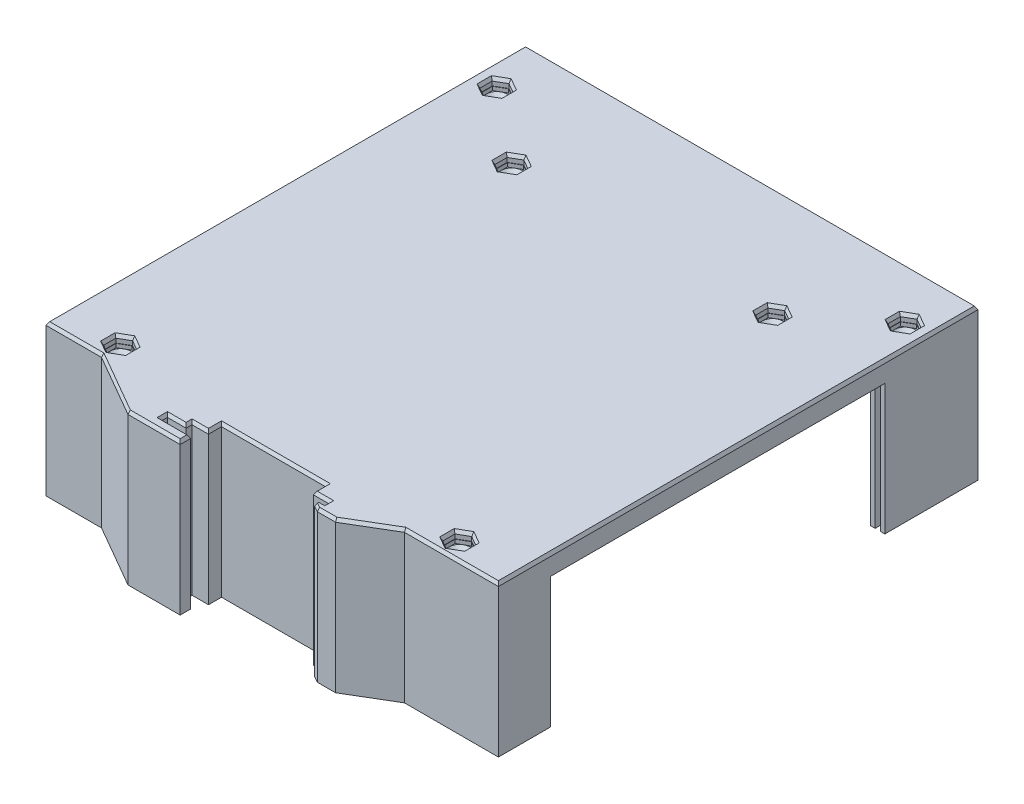
SolidWorks part; units mm, degrees
ref_plane "Спереди" through (0, 0, 0) normal (0, 0, 1) x (1, 0, 0)
ref_plane "Сверху" through (0, 0, 0) normal (0, 1, 0) x (1, 0, 0)
ref_plane "Справа" through (0, 0, 0) normal (1, 0, 0) x (0, 0, -1)
sketch "Эскиз1" plane through (0, 0, 0) normal (0, 1, 0) x (1, 0, 0)
  line L0 (0, 0) -> (0, 128.7)
  line L1 (0, 128.7) -> (121.4, 128.7)
  line L2 (121.4, 128.7) -> (121.4, 0)
  line L3 (121.4, 0) -> (0, 0)
  dimension "D1" = 128.7
  dimension "D2" = 121.4
extrude "Бобышка-Вытянуть1" add sketch "Эскиз1" along normal blind 1.5
sketch "Эскиз2" plane through (0, 0, 0) normal (0, -1, 0) x (1, 0, 0)
  line L0 (121.4, 0) -> (121.4, -128.7)
  line L1 (121.4, -128.7) -> (0, -128.7)
  line L2 (0, -128.7) -> (0, 0)
  line L3 (0, 0) -> (121.4, 0)
  line L4 (117.6, -124.9) -> (117.6, -8)
  line L5 (117.6, -8) -> (3.8, -8)
  line L6 (3.8, -8) -> (3.8, -124.9)
  line L7 (3.8, -124.9) -> (117.6, -124.9)
  line L8 (119.7, -6.3) -> (119.7, -1.7)
  line L9 (119.7, -1.7) -> (83.7, -1.7)
  line L10 (1.7, -1.7) -> (1.7, -6.3)
  line L11 (1.7, -6.3) -> (37.7, -6.3)
  line L12 (61.7, -6.3) -> (61.7, -1.7)
  line L13 (59.7, -6.3) -> (59.7, -1.7)
  line L14 (61.7, -6.3) -> (81.7, -6.3)
  line L15 (59.7, -1.7) -> (39.7, -1.7)
  line L16 (81.7, -6.3) -> (81.7, -1.7)
  line L17 (83.7, -6.3) -> (83.7, -1.7)
  line L18 (39.7, -6.3) -> (39.7, -1.7)
  line L19 (37.7, -1.7) -> (37.7, -6.3)
  line L20 (81.7, -1.7) -> (61.7, -1.7)
  line L21 (83.7, -6.3) -> (119.7, -6.3)
  line L22 (37.7, -1.7) -> (1.7, -1.7)
  line L23 (39.7, -6.3) -> (59.7, -6.3)
  line L24 (61.7, -1.7) -> (59.7, -1.7) construction
  line L25 (60.7, -1.7) -> (60.7, 0) construction
  point P28 (83.7, -4)
  dimension "D1" = 8
  dimension "D2" = 3.8
  dimension "D3" = 3.8
  dimension "D4" = 3.8
  dimension "D5" = 1.7
  dimension "D6" = 1.7
  dimension "D7" = 1.7
  dimension "D8" = 1.7
  dimension "D10" = 2
  dimension "D11" = 2
  dimension "D12" = 2
  dimension "D13" = 20
  dimension "D14" = 20
extrude "Бобышка-Вытянуть2" add sketch "Эскиз2" along normal blind 2
sketch "Эскиз3" plane through (0, -2, 0) normal (0, -1, 0) x (1, 0, 0)
  line L0 (117.6, -8) -> (121.4, -8)
  line L1 (121.4, -128.7) -> (121.4, 0) construction
  line L2 (121.4, -8) -> (121.4, -128.7)
  line L3 (121.4, -128.7) -> (0, -128.7)
  line L4 (0, -128.7) -> (0, -8)
  line L5 (0, 0) -> (0, -128.7) construction
  line L6 (0, -8) -> (3.8, -8)
  line L7 (3.8, -8) -> (3.8, -124.9)
  line L8 (3.8, -124.9) -> (117.6, -124.9)
  line L9 (117.6, -124.9) -> (117.6, -8)
  line L10 (120.3, -10.6) -> (118.8, -10.6)
  line L11 (118.8, -10.6) -> (118.8, -107.4)
  line L12 (118.8, -107.4) -> (120.3, -107.4)
  line L13 (120.3, -107.4) -> (120.3, -10.6)
  line L14 (117.6, -8) -> (3.8, -8) construction
  line L16 (117.6, -127.6) -> (3.8, -127.6)
  line L17 (117.6, -127.6) -> (117.6, -126.1)
  line L18 (117.6, -126.1) -> (3.8, -126.1)
  line L19 (3.8, -127.6) -> (3.8, -126.1)
  line L20 (2.6, -107.4) -> (1.1, -107.4)
  line L21 (2.6, -107.4) -> (2.6, -10.6)
  line L22 (2.6, -10.6) -> (1.1, -10.6)
  line L23 (1.1, -107.4) -> (1.1, -10.6)
  dimension "D1" = 2.6
  dimension "D2" = 1.5
  dimension "D3" = 1.1
  dimension "D4" = 21.3
  dimension "D5" = 3.8
  dimension "D6" = 1.1
  dimension "D7" = 1.5
  dimension "D8" = 3.8
  dimension "D9" = 21.3
  dimension "D10" = 2.6
  dimension "D11" = 1.1
  dimension "D12" = 1.5
extrude "Бобышка-Вытянуть3" add sketch "Эскиз3" along normal blind 2
sketch "Эскиз4" plane through (0, -4, 0) normal (0, -1, 0) x (1, 0, 0)
  line L0 (121.4, -8) -> (121.4, -14)
  line L1 (121.4, -128.7) -> (121.4, -8) construction
  line L2 (121.4, -14) -> (120.3, -14)
  line L3 (117.6, -124.9) -> (117.6, -8) construction
  line L4 (117.6, -14) -> (117.6, -8)
  line L5 (117.6, -8) -> (121.4, -8)
  line L6 (120.3, -14) -> (120.3, -10.6)
  line L7 (120.3, -107.4) -> (120.3, -10.6) construction
  line L8 (120.3, -10.6) -> (118.8, -10.6)
  line L9 (118.8, -10.6) -> (118.8, -14)
  line L10 (118.8, -10.6) -> (118.8, -107.4) construction
  line L11 (118.8, -14) -> (117.6, -14)
  line L12 (3.8, -8) -> (0, -8)
  line L13 (0, -8) -> (0, -14)
  line L14 (0, -8) -> (0, -128.7) construction
  line L15 (0, -14) -> (1.1, -14)
  line L16 (3.8, -8) -> (3.8, -124.9) construction
  line L17 (3.8, -14) -> (3.8, -8)
  line L18 (2.6, -14) -> (2.6, -10.6)
  line L19 (2.6, -107.4) -> (2.6, -10.6) construction
  line L20 (2.6, -10.6) -> (1.1, -10.6)
  line L21 (1.1, -10.6) -> (1.1, -14)
  line L22 (1.1, -10.6) -> (1.1, -107.4) construction
  line L23 (2.6, -14) -> (3.8, -14)
  line L24 (121.4, -128.7) -> (121.4, -103.7)
  line L25 (121.4, -103.7) -> (120.3, -103.7)
  line L26 (117.6, -8) -> (117.6, -124.9) construction
  line L27 (117.6, -103.7) -> (117.6, -124.9)
  line L28 (117.6, -124.9) -> (113.4, -124.9)
  line L29 (3.8, -124.9) -> (117.6, -124.9) construction
  line L30 (113.4, -124.9) -> (113.4, -126.1)
  line L31 (0, -128.7) -> (121.4, -128.7) construction
  line L32 (113.4, -128.7) -> (121.4, -128.7)
  line L33 (120.3, -103.7) -> (120.3, -107.4)
  line L34 (120.3, -107.4) -> (120.3, -10.6) construction
  line L35 (120.3, -107.4) -> (118.8, -107.4)
  line L36 (118.8, -107.4) -> (118.8, -103.7)
  line L37 (118.8, -10.6) -> (118.8, -107.4) construction
  line L38 (113.4, -127.6) -> (117.6, -127.6)
  line L39 (3.8, -127.6) -> (117.6, -127.6) construction
  line L40 (117.6, -127.6) -> (117.6, -126.1)
  line L41 (117.6, -126.1) -> (113.4, -126.1)
  line L42 (117.6, -126.1) -> (3.8, -126.1) construction
  line L43 (113.4, -127.6) -> (113.4, -128.7)
  line L44 (118.8, -103.7) -> (117.6, -103.7)
  line L45 (8, -124.9) -> (3.8, -124.9)
  line L46 (3.8, -124.9) -> (3.8, -103.7)
  line L47 (3.8, -103.7) -> (2.6, -103.7)
  line L48 (0, -103.7) -> (0, -128.7)
  line L49 (0, -128.7) -> (8, -128.7)
  line L50 (8, -128.7) -> (8, -127.6)
  line L51 (8, -127.6) -> (3.8, -127.6)
  line L52 (3.8, -127.6) -> (117.6, -127.6) construction
  line L53 (3.8, -127.6) -> (3.8, -126.1)
  line L54 (3.8, -126.1) -> (8, -126.1)
  line L55 (117.6, -126.1) -> (3.8, -126.1) construction
  line L56 (2.6, -103.7) -> (2.6, -107.4)
  line L57 (2.6, -107.4) -> (1.1, -107.4)
  line L58 (1.1, -107.4) -> (1.1, -103.7)
  line L59 (1.1, -10.6) -> (1.1, -107.4) construction
  line L60 (1.1, -103.7) -> (0, -103.7)
  line L61 (8, -126.1) -> (8, -124.9)
  dimension "D1" = 6
  dimension "D2" = 6
  dimension "D3" = 25
  dimension "D4" = 8
  dimension "D5" = 8
  dimension "D6" = 25
extrude "Бобышка-Вытянуть4" add sketch "Эскиз4" along normal blind 35
sketch "Эскиз5" plane through (0, 0, 0) normal (0, -1, 0) x (1, 0, 0)
  line L0 (121.4, -8) -> (121.4, 0) construction
  line L1 (0, 0) -> (0, -8) construction
  line L2 (121.4, 0) -> (0, 0) construction
  line L3 (121.4, -128.7) -> (121.4, -103.7) construction
  line L4 (0, -103.7) -> (0, -128.7) construction
  line L5 (0, -128.7) -> (8, -128.7) construction
  circle A0 centre (106.2, -4.75) radius 3.15
  circle A1 centre (15.2, -4.75) radius 3.15
  circle A2 centre (115.45, -115) radius 3.15
  circle A3 centre (5.95, -115) radius 3.15
  dimension "D1" = 6.3
  dimension "D2" = 15.2
  dimension "D3" = 15.2
  dimension "D4" = 4.75
  dimension "D5" = 5.95
  dimension "D6" = 5.95
  dimension "D7" = 13.7
extrude "Бобышка-Вытянуть5" add sketch "Эскиз5" along normal up to surface (39 mm away) up to face at (117.5, -39, -117.4429)
sketch "Эскиз6" plane through (0, 0, 0) normal (0, -1, 0) x (1, 0, 0)
  circle A0 centre (115.45, -115) radius 4.75
  circle A2 centre (106.2, -4.75) radius 4.75
  circle A3 centre (15.2, -4.75) radius 4.75
  circle A4 centre (5.95, -115) radius 4.75
  dimension "D1" = 9.5
extrude "Бобышка-Вытянуть6" add sketch "Эскиз6" along normal up to surface (4 mm away) up to face at (118.2, -4, -58.85)
sketch "Эскиз7" plane through (0, -2, 0) normal (0, -1, 0) x (1, 0, 0)
  line L0 (121.4, -8) -> (121.4, 0)
  line L1 (121.4, 0) -> (0, 0)
  line L2 (0, 0) -> (0, -8)
  line L3 (0, -8) -> (121.4, -8)
  line L4 (119.7, -6.3) -> (119.7, -1.7)
  line L5 (119.7, -1.7) -> (83.7, -1.7)
  line L6 (83.7, -1.7) -> (83.7, -6.3)
  line L7 (83.7, -6.3) -> (119.7, -6.3)
  line L8 (81.7, -6.3) -> (81.7, -1.7)
  line L9 (81.7, -1.7) -> (61.7, -1.7)
  line L10 (61.7, -1.7) -> (61.7, -6.3)
  line L11 (61.7, -6.3) -> (81.7, -6.3) construction
  line L12 (61.7, -1.7) -> (61.7, -6.3) construction
  line L13 (61.7, -6.3) -> (81.7, -6.3)
  line L14 (59.7, -6.3) -> (59.7, -1.7)
  line L15 (59.7, -1.7) -> (39.7, -1.7)
  line L16 (39.7, -1.7) -> (39.7, -6.3)
  line L17 (39.7, -6.3) -> (59.7, -6.3)
  line L18 (37.7, -6.3) -> (37.7, -1.7)
  line L19 (37.7, -1.7) -> (1.7, -1.7)
  line L20 (1.7, -1.7) -> (1.7, -6.3)
  line L21 (1.7, -6.3) -> (37.7, -6.3)
extrude "Бобышка-Вытянуть7" add sketch "Эскиз7" along normal up to surface (37 mm away) up to face at (119.525, -39, -11.65)
sketch "Эскиз8" plane through (0, -39, 0) normal (0, -1, 0) x (1, 0, 0)
  line L0 (83.7, -8) -> (83.7, -1.7)
  line L1 (83.7, -1.7) -> (81.7, -1.7)
  line L2 (81.7, -1.7) -> (81.7, -6.3)
  line L4 (39.7, -6.3) -> (39.7, -1.7)
  line L5 (39.7, -1.7) -> (37.7, -1.7)
  line L6 (37.7, -1.7) -> (37.7, -8)
  line L8 (81.7, -6.3) -> (39.7, -6.3)
  line L9 (37.7, -8) -> (83.7, -8)
  line L11 (117.6, -8) -> (3.8, -8) construction
extrude "Бобышка-Вытянуть15" add sketch "Эскиз8" along normal blind 3.8
sketch "Эскиз9" plane through (0, 0, 0) normal (0, -1, 0) x (1, 0, 0)
  line L0 (3.8, -124.9) -> (117.6, -124.9) construction
  line L1 (61.8, -124.9) -> (59.6, -124.9)
  line L2 (61.8, -124.9) -> (61.8, -122.7)
  line L3 (61.8, -122.7) -> (59.6, -122.7)
  line L4 (59.6, -124.9) -> (59.6, -122.7)
  line L5 (117.6, -110.7644) -> (117.6, -8) construction
  line L6 (104, -124.9) -> (101.8, -124.9)
  line L7 (104, -124.9) -> (104, -122.7)
  line L8 (104, -122.7) -> (101.8, -122.7)
  line L9 (101.8, -124.9) -> (101.8, -122.7)
  line L10 (19.6, -124.9) -> (17.4, -124.9)
  line L11 (19.6, -124.9) -> (19.6, -122.7)
  line L12 (19.6, -122.7) -> (17.4, -122.7)
  line L13 (17.4, -124.9) -> (17.4, -122.7)
  line L14 (117.6, -100.4) -> (115.4, -100.4)
  line L15 (117.6, -100.4) -> (117.6, -98.2)
  line L16 (117.6, -98.2) -> (115.4, -98.2)
  line L17 (115.4, -100.4) -> (115.4, -98.2)
  line L18 (117.6, -8) -> (83.7, -8) construction
  line L19 (117.6, -16) -> (115.4, -16)
  line L20 (117.6, -16) -> (117.6, -18.2)
  line L21 (117.6, -18.2) -> (115.4, -18.2)
  line L22 (115.4, -16) -> (115.4, -18.2)
  line L23 (61.8, -8) -> (59.6, -8)
  line L24 (61.8, -8) -> (61.8, -10.2)
  line L25 (61.8, -10.2) -> (59.6, -10.2)
  line L26 (59.6, -8) -> (59.6, -10.2)
  line L27 (3.8, -8) -> (3.8, -110.7644) construction
  line L28 (3.8, -16) -> (6, -16)
  line L29 (3.8, -16) -> (3.8, -18.2)
  line L30 (3.8, -18.2) -> (6, -18.2)
  line L31 (6, -16) -> (6, -18.2)
  line L32 (95.7, -99.24) -> (25.7, -99.24) construction
  line L33 (3.8, -100.4) -> (6, -100.4)
  line L34 (3.8, -100.4) -> (3.8, -98.2)
  line L35 (3.8, -98.2) -> (6, -98.2)
  line L36 (6, -100.4) -> (6, -98.2)
  line L37 (60.7, -8) -> (60.7, 0) construction
  line L38 (0, 0) -> (121.4, 0) construction
  line L39 (117.6, -8) -> (109.6641, -8) construction
  line L42 (8, -128.7) -> (113.4, -128.7) construction
  line L43 (60.7, -128.7) -> (60.7, -99.24) construction
  circle A0 centre (95.7, -99.24) radius 4.75
  circle A1 centre (25.7, -99.24) radius 4.75
  point P40 (116.5, -98.2)
  point P41 (116.5, -18.2)
  point P46 (6, -17.1)
  point P49 (116.5, -16)
  dimension "D15" = 9.5
  dimension "D1" = 2.2
  dimension "D2" = 2.2
  dimension "D3" = 2.2
  dimension "D4" = 2.2
  dimension "D5" = 2.2
  dimension "D6" = 2.2
  dimension "D7" = 40
  dimension "D8" = 40
  dimension "D9" = 2.2
  dimension "D10" = 2.2
  dimension "D11" = 2.2
  dimension "D12" = 2.2
  dimension "D13" = 8
  dimension "D14" = 80
  dimension "D16" = 70
  dimension "D17" = 29.46
extrude "Бобышка-Вытянуть9" add sketch "Эскиз9" along normal up to surface (4 mm away) up to face at (118.2, -4, -58.85)
sketch "Эскиз10" plane through (0, 1.5, 0) normal (0, 1, 0) x (1, 0, 0)
  circle A0 centre (5.95, 115) radius 1.75
  circle A1 centre (115.45, 115) radius 1.75
  circle A2 centre (15.2, 4.75) radius 1.75
  circle A3 centre (106.2, 4.75) radius 1.75
  circle A4 centre (25.7, 99.24) radius 1.75
  circle A5 centre (95.7, 99.24) radius 1.75
  dimension "D1" = 3.5
extrude "Вырез-Вытянуть1" cut sketch "Эскиз10" against normal up to surface (40.5 mm away) up to face at (117.1813, -39, -117.1375)
sketch "Эскиз11" plane through (0, 1.5, 0) normal (0, 1, 0) x (1, 0, 0)
  line L0 (3.1, 116.6454) -> (3.1, 113.3546)
  line L1 (3.1, 113.3546) -> (5.95, 111.7091)
  line L2 (5.95, 111.7091) -> (8.8, 113.3546)
  line L3 (8.8, 113.3546) -> (8.8, 116.6454)
  line L4 (8.8, 116.6454) -> (5.95, 118.2909)
  line L5 (5.95, 118.2909) -> (3.1, 116.6454)
  line L6 (5.95, 115) -> (8.8, 115) construction
  line L7 (112.6, 116.6454) -> (112.6, 113.3546)
  line L8 (112.6, 113.3546) -> (115.45, 111.7091)
  line L9 (115.45, 111.7091) -> (118.3, 113.3546)
  line L10 (118.3, 113.3546) -> (118.3, 116.6454)
  line L11 (118.3, 116.6454) -> (115.45, 118.2909)
  line L12 (115.45, 118.2909) -> (112.6, 116.6454)
  line L13 (115.45, 115) -> (118.3, 115) construction
  line L14 (22.85, 100.8854) -> (22.85, 97.5946)
  line L15 (22.85, 97.5946) -> (25.7, 95.9491)
  line L16 (25.7, 95.9491) -> (28.55, 97.5946)
  line L17 (28.55, 97.5946) -> (28.55, 100.8854)
  line L18 (28.55, 100.8854) -> (25.7, 102.5309)
  line L19 (25.7, 102.5309) -> (22.85, 100.8854)
  line L20 (25.7, 99.24) -> (28.55, 99.24) construction
  line L27 (95.7, 99.24) -> (92.85, 99.24) construction
  line L28 (12.35, 4.75) -> (15.2, 4.75) construction
  line L29 (98.55, 100.8854) -> (95.7, 102.5309)
  line L30 (95.7, 102.5309) -> (92.85, 100.8854)
  line L31 (92.85, 100.8854) -> (92.85, 97.5946)
  line L32 (92.85, 97.5946) -> (95.7, 95.9491)
  line L33 (95.7, 95.9491) -> (98.55, 97.5946)
  line L34 (98.55, 97.5946) -> (98.55, 100.8854)
  line L35 (18.05, 6.3954) -> (15.2, 8.0409)
  line L36 (15.2, 8.0409) -> (12.35, 6.3954)
  line L37 (12.35, 6.3954) -> (12.35, 3.1046)
  line L38 (12.35, 3.1046) -> (15.2, 1.4591)
  line L39 (15.2, 1.4591) -> (18.05, 3.1046)
  line L40 (18.05, 3.1046) -> (18.05, 6.3954)
  line L41 (106.2, 4.75) -> (103.35, 4.75) construction
  line L42 (109.05, 6.3954) -> (106.2, 8.0409)
  line L43 (106.2, 8.0409) -> (103.35, 6.3954)
  line L44 (103.35, 6.3954) -> (103.35, 3.1046)
  line L45 (103.35, 3.1046) -> (106.2, 1.4591)
  line L46 (106.2, 1.4591) -> (109.05, 3.1046)
  line L47 (109.05, 3.1046) -> (109.05, 6.3954)
  circle A0 centre (95.7, 99.24) radius 2.85 construction
  circle A2 centre (95.7, 99.24) radius 1.75 construction
  circle A3 centre (15.2, 4.75) radius 2.85 construction
  circle A4 centre (106.2, 4.75) radius 2.85 construction
  point P0 (5.95, 115)
  point P16 (25.7, 99.24)
  point P19 (15.2, 4.75)
  point P21 (106.2, 4.75)
  point P23 (115.45, 115)
  dimension "D16" = 5.7
  dimension "D17" = 5.7
  dimension "D18" = 5.7
  dimension "D1" = 5.7
  dimension "D2" = 120
  dimension "D3" = 120
  dimension "D4" = 2.85
  dimension "D5" = 5.7
  dimension "D6" = 5.7
  dimension "D7" = 2.85
  dimension "D8" = 120
  dimension "D9" = 120
  dimension "D10" = 5.7
  dimension "D11" = 5.7
  dimension "D12" = 2.85
  dimension "D13" = 120
  dimension "D14" = 120
  dimension "D15" = 5.7
extrude "Вырез-Вытянуть2" cut sketch "Эскиз11" against normal blind 3
sketch "Эскиз12" plane through (0, 1.5, 0) normal (0, 1, 0) x (1, 0, 0)
  line L11 (121.4, 14) -> (121.4, 0) construction
  line L13 (96.2, 0) -> (75.3, 0)
  line L14 (84.6, -6.9) -> (96.2, 0)
  line L15 (79.7, -6.9) -> (84.6, -6.9)
  line L16 (78.1, -6) -> (79.7, -6.9)
  line L17 (78.1, -4.9) -> (78.1, -6)
  line L18 (79.7, -4.9) -> (78.1, -4.9)
  line L19 (79.7, -3.5) -> (79.7, -4.9)
  line L20 (75.3, -3.5) -> (79.7, -3.5)
  line L21 (75.3, 0) -> (75.3, -3.5)
  line L23 (0, 0) -> (121.4, 0) construction
  dimension "D1" = 46.1
  dimension "D2" = 3.5
  dimension "D3" = 1.4
  dimension "D4" = 4.4
  dimension "D5" = 1.6
  dimension "D6" = 0.9
  dimension "D7" = 2
  dimension "D8" = 1.6
  dimension "D9" = 11.6
  dimension "D10" = 20.9
extrude "Бобышка-Вытянуть10" add sketch "Эскиз12" against normal up to surface (40.5 mm away) up to face at (15.2, -39, -6.5)
sketch "Эскиз13" plane through (0, 1.5, 0) normal (0, 1, 0) x (1, 0, 0)
  line L3 (79.7, -4.9) -> (79.7, -3.5) construction
  line L15 (0, 0) -> (75.3, 0) construction
  line L17 (31.7, -9.7) -> (14.8991, 0)
  line L18 (37.7, -5.1) -> (42.7, -5.1)
  line L19 (37.7, -6.9) -> (37.7, -5.1)
  line L20 (45.7, -6.9) -> (37.7, -6.9)
  line L21 (45.7, -9.7) -> (45.7, -6.9)
  line L22 (31.7, -9.7) -> (45.7, -9.7)
  line L23 (47.1, 0) -> (14.8991, 0)
  line L24 (47.1, -3.5) -> (47.1, 0)
  line L25 (42.7, -3.5) -> (47.1, -3.5)
  line L26 (42.7, -5.1) -> (42.7, -3.5)
  line L27 (79.7, -3.5) -> (75.3, -3.5) construction
  dimension "D1" = 32.2009
  dimension "D2" = 4.4
  dimension "D3" = 5
  dimension "D4" = 8
  dimension "D5" = 14
  dimension "D6" = 1.6
  dimension "D7" = 1.8
  dimension "D8" = 2.8
  dimension "D9" = 37
extrude "Бобышка-Вытянуть11" add sketch "Эскиз13" against normal up to surface (40.5 mm away) up to face at (15.2, -39, -6.5)
ref_plane "Плоскость1" through (0, -18.75, 0) normal (0, 1, 0) x (1, 0, 0)
sketch "Эскиз14" plane through (0, -18.75, 0) normal (0, 1, 0) x (1, 0, 0)
  line L0 (41.7, -6.9) -> (41.7, -5.9)
  line L5 (41.7, -6.9) -> (41.7, -5.9) construction
  line L6 (37.7, -6.9) -> (45.7, -6.9) construction
  line L7 (41.7, -6.9) -> (39.5, -6.9)
  line L8 (39.5, -6.9) -> (41.7, -5.9)
  dimension "D3" = 2.2
  dimension "D4" = 1
revolve "Повернуть1" add sketch "Эскиз14" angle 360 about L5
chamfer "Фаска2" distance 1 angle 45 6 edges at (15.2, -1.5, -3) (106.2, -1.5, -3) (115.45, -1.5, -113.25) (95.7, -1.5, -97.49) (25.7, -1.5, -97.49) (5.95, -1.5, -113.25)
chamfer "Фаска3" distance 0.5 angle 60 23 edges at (60.7, 1.5, -128.7) (0, 1.5, -64.35) (7.4496, 1.5, 0) (108.8, 1.5, 0) (90.4, 1.5, 3.45) (75.3, 1.5, 1.75) (77.5, 1.5, 3.5) (79.7, 1.5, 4.2) (78.9, 1.5, 4.9) (78.1, 1.5, 5.45) (78.9, 1.5, 6.45) (82.15, 1.5, 6.9) (61.2, 1.5, 0) (38.7, 1.5, 9.7) (45.7, 1.5, 8.3) (41.7, 1.5, 6.9) (37.7, 1.5, 6) (40.2, 1.5, 5.1) (42.7, 1.5, 4.3) (44.9, 1.5, 3.5) (47.1, 1.5, 1.75) (23.2996, 1.5, 4.85) (121.4, 1.5, -64.35)
chamfer "Фаска4" distance 0.5 angle 60 36 edges at (4.525, 1.5, -117.4682) (3.1, 1.5, -115) (4.525, 1.5, -112.5318) (7.375, 1.5, -112.5318) (8.8, 1.5, -115) (7.375, 1.5, -117.4682) (24.275, 1.5, -101.7082) (22.85, 1.5, -99.24) (24.275, 1.5, -96.7718) (27.125, 1.5, -96.7718) (28.55, 1.5, -99.24) (27.125, 1.5, -101.7082) (116.875, 1.5, -112.5318) (114.025, 1.5, -112.5318) (112.6, 1.5, -115) (114.025, 1.5, -117.4682) (116.875, 1.5, -117.4682) (118.3, 1.5, -115) (98.55, 1.5, -99.24) (97.125, 1.5, -96.7718) (94.275, 1.5, -96.7718) (92.85, 1.5, -99.24) (94.275, 1.5, -101.7082) (97.125, 1.5, -101.7082) (107.625, 1.5, -2.2818) (104.775, 1.5, -2.2818) (103.35, 1.5, -4.75) (104.775, 1.5, -7.2182) (107.625, 1.5, -7.2182) (109.05, 1.5, -4.75) (12.35, 1.5, -4.75) (13.775, 1.5, -7.2182) (16.625, 1.5, -7.2182) (18.05, 1.5, -4.75) (16.625, 1.5, -2.2818) (13.775, 1.5, -2.2818)
sketch "Эскиз15" plane through (0, 0, 0) normal (0, -1, 0) x (1, 0, 0)
  line L0 (8, -124.9) -> (3.8, -124.9)
  line L1 (3.8, -124.9) -> (3.8, -119.2356)
  line L2 (3.8, -119.2356) -> (8, -124.9)
  line L3 (113.4, -124.9) -> (117.6, -124.9)
  line L4 (117.6, -124.9) -> (117.6, -119.2356)
  line L5 (117.6, -119.2356) -> (113.4, -124.9)
extrude "Бобышка-Вытянуть12" add sketch "Эскиз15" along normal up to surface (39 mm away) up to face at (5.95, -39, -116.75)
ref_plane "Плоскость2" through (79.8, 0, 0) normal (1, 0, 0) x (0, 0, -1)
ref_plane "Плоскость3" through (41.6, 0, 0) normal (-1, 0, 0) x (0, 0, 1)
sketch "Эскиз16" plane through (79.8, 0, 0) normal (1, 0, 0) x (0, 0, -1)
  line L0 (8, -4) -> (9.65, -7)
  line L1 (9.65, -7) -> (8, -10)
  line L2 (8, -39) -> (8, 0) construction
  line L3 (8, -10) -> (8, -4)
  dimension "D1" = 1.65
  dimension "D2" = 3
  dimension "D3" = 3
extrude "Бобышка-Вытянуть13" add sketch "Эскиз16" along normal blind 2.2 and the other way blind 2.2
sketch "Эскиз18" plane through (41.6, 0, 0) normal (-1, 0, 0) x (0, 0, 1)
  line L0 (-8, -4) -> (-9.65, -7)
  line L1 (-8, -4) -> (-8, 0) construction
  line L2 (-10.2, -4) -> (-8, -4) construction
  line L3 (-9.65, -7) -> (-8, -4) construction
  line L4 (-9.65, -7) -> (-8, -10)
  line L5 (-8, -39) -> (-8, 0) construction
  line L6 (-8, -10) -> (-8, -4)
  line L7 (-8, -10) -> (-9.65, -7) construction
extrude "Бобышка-Вытянуть14" add sketch "Эскиз18" along normal blind 2.2 and the other way blind 2.2
sketch "Эскиз19" plane through (0, -1.5, 0) normal (0, 1, 0) x (1, 0, 0)
  line L0 (103.35, 3.1046) -> (106.2, 1.4591) construction
  line L1 (112.7, 113.4123) -> (115.45, 111.8246)
  line L2 (115.45, 111.8246) -> (118.2, 113.4123)
  line L3 (118.2, 113.4123) -> (118.2, 116.5877)
  line L4 (118.2, 116.5877) -> (115.45, 118.1754)
  line L5 (115.45, 118.1754) -> (112.7, 116.5877)
  line L6 (112.7, 116.5877) -> (112.7, 113.4123)
  line L7 (92.95, 97.6523) -> (95.7, 96.0646)
  line L8 (95.7, 96.0646) -> (98.45, 97.6523)
  line L9 (98.45, 97.6523) -> (98.45, 100.8277)
  line L10 (98.45, 100.8277) -> (95.7, 102.4154)
  line L11 (95.7, 102.4154) -> (92.95, 100.8277)
  line L12 (92.95, 100.8277) -> (92.95, 97.6523)
  line L13 (3.2, 113.4123) -> (5.95, 111.8246)
  line L14 (5.95, 111.8246) -> (8.7, 113.4123)
  line L15 (8.7, 113.4123) -> (8.7, 116.5877)
  line L16 (8.7, 116.5877) -> (5.95, 118.1754)
  line L17 (5.95, 118.1754) -> (3.2, 116.5877)
  line L18 (3.2, 116.5877) -> (3.2, 113.4123)
  line L19 (22.95, 97.6523) -> (25.7, 96.0646)
  line L20 (25.7, 96.0646) -> (28.45, 97.6523)
  line L21 (28.45, 97.6523) -> (28.45, 100.8277)
  line L22 (28.45, 100.8277) -> (25.7, 102.4154)
  line L23 (25.7, 102.4154) -> (22.95, 100.8277)
  line L24 (22.95, 100.8277) -> (22.95, 97.6523)
  line L25 (12.45, 3.1623) -> (15.2, 1.5746)
  line L26 (15.2, 1.5746) -> (17.95, 3.1623)
  line L27 (17.95, 3.1623) -> (17.95, 6.3377)
  line L28 (17.95, 6.3377) -> (15.2, 7.9254)
  line L29 (15.2, 7.9254) -> (12.45, 6.3377)
  line L30 (12.45, 6.3377) -> (12.45, 3.1623)
  line L31 (103.45, 3.1623) -> (106.2, 1.5746)
  line L32 (106.2, 1.5746) -> (108.95, 3.1623)
  line L33 (108.95, 3.1623) -> (108.95, 6.3377)
  line L34 (108.95, 6.3377) -> (106.2, 7.9254)
  line L35 (106.2, 7.9254) -> (103.45, 6.3377)
  line L36 (103.45, 6.3377) -> (103.45, 3.1623)
  line L37 (12.35, 3.1046) -> (15.2, 1.4591) construction
  line L38 (3.1, 113.3546) -> (5.95, 111.7091) construction
  line L39 (22.85, 97.5946) -> (25.7, 95.9491) construction
  line L40 (92.85, 97.5946) -> (95.7, 95.9491) construction
  line L41 (112.6, 113.3546) -> (115.45, 111.7091) construction
  line L42 (112.6, 113.3546) -> (115.45, 111.7091) construction
  line L43 (112.6, 113.3546) -> (115.45, 111.7091)
  line L44 (115.45, 111.7091) -> (118.3, 113.3546)
  line L45 (118.3, 113.3546) -> (118.3, 116.6454)
  line L46 (118.3, 116.6454) -> (115.45, 118.2909)
  line L47 (115.45, 118.2909) -> (112.6, 116.6454)
  line L48 (112.6, 116.6454) -> (112.6, 113.3546)
  line L49 (92.85, 97.5946) -> (95.7, 95.9491) construction
  line L50 (92.85, 97.5946) -> (95.7, 95.9491)
  line L51 (95.7, 95.9491) -> (98.55, 97.5946)
  line L52 (98.55, 97.5946) -> (98.55, 100.8854)
  line L53 (98.55, 100.8854) -> (95.7, 102.5309)
  line L54 (95.7, 102.5309) -> (92.85, 100.8854)
  line L55 (92.85, 100.8854) -> (92.85, 97.5946)
  line L56 (12.35, 3.1046) -> (15.2, 1.4591) construction
  line L57 (22.85, 97.5946) -> (25.7, 95.9491)
  line L58 (25.7, 95.9491) -> (28.55, 97.5946)
  line L59 (28.55, 97.5946) -> (28.55, 100.8854)
  line L60 (28.55, 100.8854) -> (25.7, 102.5309)
  line L61 (25.7, 102.5309) -> (22.85, 100.8854)
  line L62 (22.85, 100.8854) -> (22.85, 97.5946)
  line L63 (3.1, 113.3546) -> (5.95, 111.7091)
  line L64 (5.95, 111.7091) -> (8.8, 113.3546)
  line L65 (8.8, 113.3546) -> (8.8, 116.6454)
  line L66 (8.8, 116.6454) -> (5.95, 118.2909)
  line L67 (5.95, 118.2909) -> (3.1, 116.6454)
  line L68 (3.1, 116.6454) -> (3.1, 113.3546)
  line L69 (12.35, 3.1046) -> (15.2, 1.4591)
  line L70 (15.2, 1.4591) -> (18.05, 3.1046)
  line L71 (18.05, 3.1046) -> (18.05, 6.3954)
  line L72 (18.05, 6.3954) -> (15.2, 8.0409)
  line L73 (15.2, 8.0409) -> (12.35, 6.3954)
  line L74 (12.35, 6.3954) -> (12.35, 3.1046)
  line L76 (103.35, 3.1046) -> (106.2, 1.4591)
  line L77 (106.2, 1.4591) -> (109.05, 3.1046)
  line L78 (109.05, 3.1046) -> (109.05, 6.3954)
  line L79 (109.05, 6.3954) -> (106.2, 8.0409)
  line L80 (106.2, 8.0409) -> (103.35, 6.3954)
  line L81 (103.35, 6.3954) -> (103.35, 3.1046)
  circle A0 centre (115.45, 115) radius 2.75 construction
  circle A1 centre (95.7, 99.24) radius 2.75 construction
  circle A2 centre (5.95, 115) radius 2.75 construction
  circle A3 centre (25.7, 99.24) radius 2.75 construction
  circle A4 centre (15.2, 4.75) radius 2.75 construction
  circle A5 centre (106.2, 4.75) radius 2.75 construction
  circle A6 centre (115.45, 115) radius 2.85 construction
  circle A7 centre (95.7, 99.24) radius 2.85 construction
  circle A8 centre (25.7, 99.24) radius 2.85 construction
  circle A9 centre (5.95, 115) radius 2.85 construction
  circle A10 centre (15.2, 4.75) radius 2.85 construction
  circle A11 centre (106.2, 4.75) radius 2.85 construction
  dimension "D1" = 5.5
extrude "Бобышка-Вытянуть16" add sketch "Эскиз19" along normal blind 1
